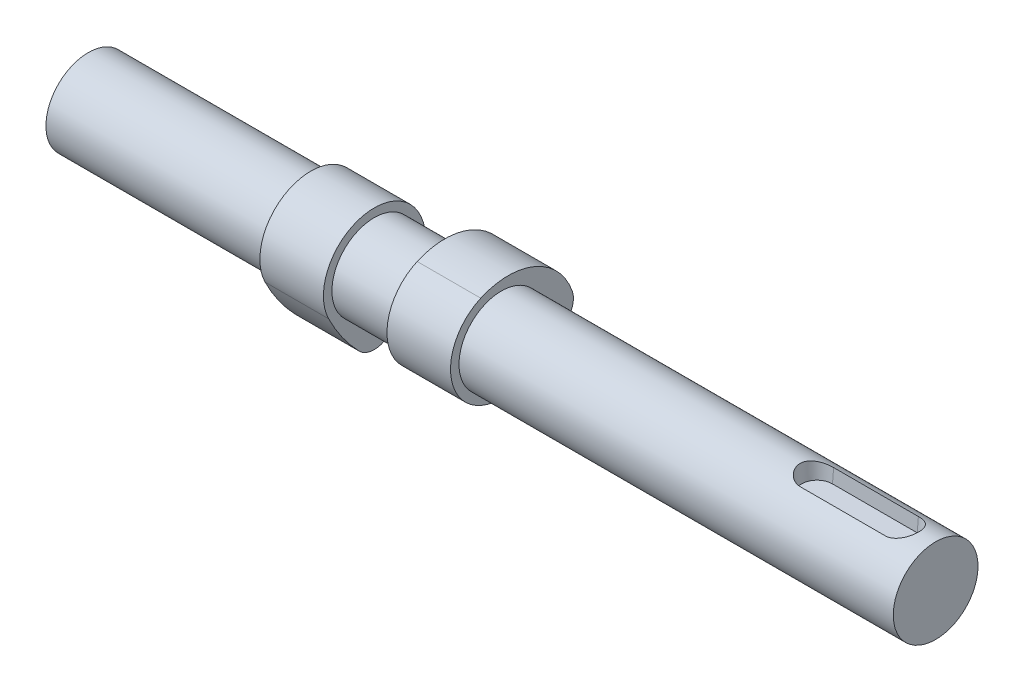
SolidWorks part; units mm, degrees
material "Gray Cast Iron"
ref_plane "Front Plane" through (0, 0, 0) normal (0, 0, 1) x (1, 0, 0)
ref_plane "Top Plane" through (0, 0, 0) normal (0, 1, 0) x (1, 0, 0)
ref_plane "Right Plane" through (0, 0, 0) normal (1, 0, 0) x (0, 0, -1)
sketch "Sketch2" plane through (0, 0, 0) normal (1, 0, 0) x (0, 0, -1)
  circle A0 centre (0, 0) radius 10
  dimension "D1" = 20
extrude "Boss-Extrude1" add sketch "Sketch2" along normal blind 125 and the other way blind 75
sketch "Sketch3" plane through (0, 0, 0) normal (1, 0, 0) x (0, 0, -1)
  arc A0 (-4.8671, 10.9687) -> (5.3062, -10.7631) centre (0, 0) ccw
  arc A1 (-4.8671, 10.9687) -> (16.7127, 1.6619) centre (1.6224, -3.6562) cw
  arc A2 (5.3062, -10.7631) -> (15.4795, -3.5877) centre (-12.3812, 25.1139) ccw
  arc A3 (16.7127, 1.6619) -> (15.4795, -3.5877) centre (11.997, 0) cw
  dimension "D1" = 5
  dimension "D2" = 24
  dimension "D3" = 40
  dimension "D4" = 16
  dimension "D5" = 12.5
extrude "Boss-Extrude2" add sketch "Sketch3" along normal mid plane 15 from offset 15 separate body
mirror "Mirror1" about plane through (0, 0, 0) normal (1, 0, 0) of bodies 102
move or copy body "Body-Move/Copy1" bodies to move or copy 103 copy no rotation origin (0, 0, 0) rotation axis (-1, 0, 0) rotation angle 90 parameters "Angle Around Edge"=270
sketch "Sketch4" plane through (0, 0, 0) normal (0, 1, 0) x (1, 0, 0)
  line L0 (125, 0) -> (99.611, 0) construction
  line L1 (125, -10) -> (125, 10) construction
  line L2 (97, 0) -> (117, 0) construction
  line L3 (97, 4) -> (117, 4)
  line L4 (97, -4) -> (117, -4)
  arc A0 (97, 4) -> (97, -4) centre (97, 0) ccw
  arc A1 (117, -4) -> (117, 4) centre (117, 0) ccw
  point P7 (107, 0)
  dimension "D1" = 4
  dimension "D2" = 20
  dimension "D3" = 8
extrude "Cut-Extrude1" cut sketch "Sketch4" against normal blind 4 draft 5 from offset 10
